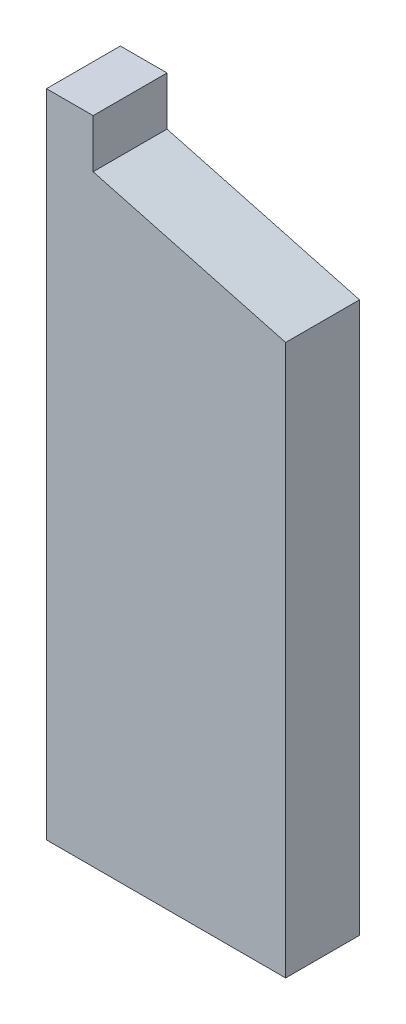
SolidWorks part; units mm, degrees
ref_plane "前视基准面" through (0, 0, 0) normal (0, 0, 1) x (1, 0, 0)
ref_plane "上视基准面" through (0, 0, 0) normal (0, 1, 0) x (1, 0, 0)
ref_plane "右视基准面" through (0, 0, 0) normal (1, 0, 0) x (0, 0, -1)
sketch "草图1" plane through (0, 0, 0) normal (0, 0, 1) x (1, 0, 0)
  line L1 (0, 0) -> (24.6, 0)
  line L2 (0, 0) -> (0, -66.915)
  line L3 (0, -66.915) -> (24.6, -66.915)
  line L4 (24.6, 0) -> (24.6, -66.915)
  line L5 (4.8, 0) -> (19.8, 0)
  line L6 (4.8, 0) -> (4.8, -5)
  line L7 (4.8, -5) -> (19.8, -5)
  line L8 (19.8, 0) -> (19.8, -5)
  point P9 (12.3, 0)
  dimension "D1" = 5
  dimension "D2" = 24.6
  dimension "D3" = 15
  dimension "D4" = 61.915
extrude "凸台-拉伸1" add sketch "草图1" along normal blind 7.6 contours L1 L8 L7 L6 L2 L3 L4
draft "拔模5" [suppressed] type of draft neutral plane draft angle 15 faces to draft 1 parameters "D1"=15
sketch "草图2" plane through (0, 0, 7.6) normal (0, 0, 1) x (1, 0, 0)
  line L0 (4.8, -5) -> (24.6, -10.3054)
  line L1 (24.6, 0) -> (24.6, -66.915) construction
  line L2 (4.8, -5) -> (19.8, -5) construction
  dimension "D1" = 15
extrude "切除-拉伸1" cut sketch "草图2" against normal through all and the other way through all
